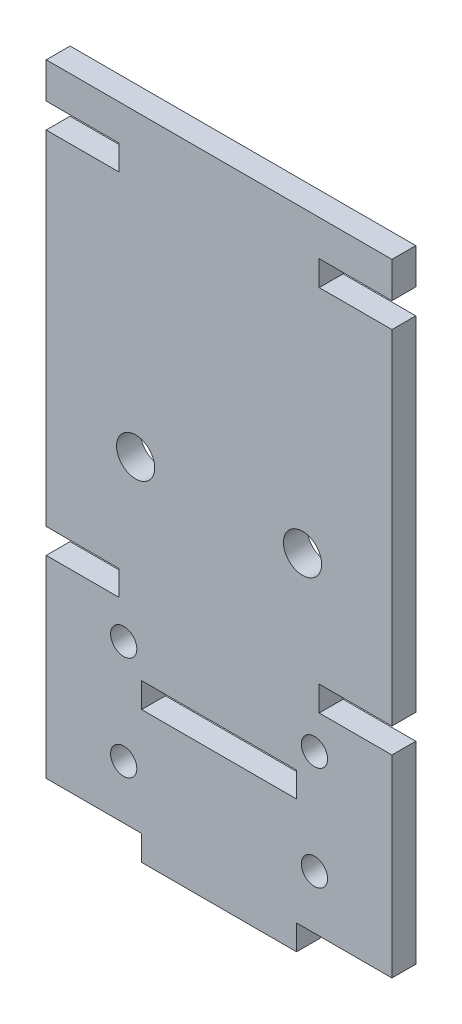
SolidWorks part; units mm, degrees
ref_plane "前视基准面" through (0, 0, 0) normal (0, 0, 1) x (1, 0, 0)
ref_plane "上视基准面" through (0, 0, 0) normal (0, 1, 0) x (1, 0, 0)
ref_plane "右视基准面" through (0, 0, 0) normal (1, 0, 0) x (0, 0, -1)
other "Configuration Table"
sketch "草图1" plane through (0, 0, 0) normal (0, 0, 1) x (1, 0, 0)
  line L0 (-12.2429, -15.7995) -> (16.7571, -15.7995)
  line L1 (16.7571, -15.7995) -> (16.7571, 31.3005)
  line L2 (16.7571, 31.3005) -> (-12.2429, 31.3005)
  line L3 (-12.2429, 31.3005) -> (-12.2429, -15.7995)
  line L4 (34.6769, 7.7505) -> (-34.6769, 7.7505) construction
  line L5 (2.2571, 33.4458) -> (2.2571, -33.4458) construction
  line L6 (-4.2429, -15.7995) -> (-4.2429, -17.8995)
  line L7 (-4.2429, -17.8995) -> (8.7571, -17.8995)
  line L8 (8.7571, -15.7995) -> (8.7571, -17.8995)
  line L9 (-4.2429, -4.6995) -> (-12.2429, -4.6995)
  line L10 (-4.2429, -4.6995) -> (-4.2429, -6.7995)
  line L11 (-4.2429, -6.7995) -> (-12.2429, -6.7995)
  line L12 (8.7571, -6.7995) -> (16.7571, -6.7995)
  line L13 (8.7571, -4.6995) -> (16.7571, -4.6995)
  line L14 (8.7571, -4.6995) -> (8.7571, -6.7995)
  line L15 (-4.2429, -6.7995) -> (8.7571, -6.7995)
  line L16 (-4.2429, -4.6995) -> (8.7571, -4.6995)
  point P12 (2.2571, -17.8995)
  dimension "D1" = 29
  dimension "D2" = 2.1
  dimension "D3" = 8
  dimension "D4" = 2.1
  dimension "D5" = 9
  dimension "D6" = 36
extrude "凸台-拉伸1" add sketch "草图1" along normal blind 2 contours L9 L16 L13 L1 L2 L3 | L15 L11 L3 L0 L1 L12 | L13 L14 L12 L1 | L11 L10 L9 L3 | L8 L0 L6 L7
sketch "草图2" plane through (0, 0, 2) normal (0, 0, 1) x (1, 0, 0)
  line L0 (2.2571, -4.6995) -> (2.2571, 37.8444) construction
  line L1 (8.7571, -4.6995) -> (-4.2429, -4.6995) construction
  line L2 (16.7571, 2.5005) -> (10.6571, 2.5005)
  line L3 (16.7571, -15.7995) -> (16.7571, 31.3005) construction
  line L4 (10.6571, 2.5005) -> (10.6571, 0.4005)
  line L5 (10.6571, 0.4005) -> (16.7571, 0.4005)
  line L7 (-6.1429, 2.5005) -> (-6.1429, 0.4005)
  line L8 (-6.1429, 0.4005) -> (-12.2429, 0.4005)
  line L9 (-6.1429, 2.5005) -> (-12.2429, 2.5005)
  line L10 (-12.2429, 31.3005) -> (-12.2429, -15.7995) construction
  line L11 (-12.2429, 2.5005) -> (-12.2429, 0.4005)
  line L12 (16.7571, 2.5005) -> (16.7571, 0.4005)
  dimension "D1" = 2.1
  dimension "D2" = 6.1
  dimension "D3" = 5.1
extrude "切除-拉伸1" cut sketch "草图2" against normal blind 2 contours L11 L8 L7 L9 | L12 L5 L4 L2
sketch "草图3" plane through (0, 0, 2) normal (0, 0, 1) x (1, 0, 0)
  line L0 (-6.1429, 31.3005) -> (-6.1429, 33.4005)
  line L1 (16.7571, 31.3005) -> (-12.2429, 31.3005) construction
  line L2 (-6.1429, 33.4005) -> (10.6571, 33.4005)
  line L3 (2.2571, 31.3005) -> (2.2571, 42.1871) construction
  line L4 (10.6571, 31.3005) -> (10.6571, 33.4005)
  line L5 (-6.1429, 31.3005) -> (10.6571, 31.3005)
  point P10 (2.2571, 33.4005)
  dimension "D1" = 2.1
  dimension "D2" = 16.8
extrude "凸台-拉伸2" add sketch "草图3" against normal blind 2 contours L5 L4 L2 L0
sketch "草图4" plane through (0, 0, 2) normal (0, 0, 1) x (1, 0, 0)
  line L0 (2.2571, -4.6995) -> (2.2571, 42.1555) construction
  line L1 (8.7571, -4.6995) -> (-4.2429, -4.6995) construction
  line L2 (-6.1429, 31.3005) -> (-12.2429, 31.3005) construction
  circle A0 centre (-4.7429, 11.3005) radius 1.6
  circle A1 centre (9.2571, 11.3005) radius 1.6
  dimension "D1" = 3.2
  dimension "D2" = 14
  dimension "D3" = 20
extrude "切除-拉伸2" cut sketch "草图4" against normal blind 2
sketch "草图5" plane through (0, 0, 0) normal (0, 0, -1) x (-1, 0, 0)
  circle A0 centre (-10.2571, -2.5995) radius 1.1
  circle A1 centre (5.7429, -2.5995) radius 1.1
extrude "切除-拉伸5" cut sketch "草图5" against normal blind 10
sketch "草图6" plane through (0, 0, 2) normal (0, 0, 1) x (1, 0, 0)
  line L0 (2.2571, -4.6995) -> (2.2571, -22.9249) construction
  line L1 (8.7571, -4.6995) -> (-4.2429, -4.6995) construction
  line L2 (23.045, -11.2995) -> (-21.3219, -11.2995) construction
  line L3 (-4.2429, -6.7995) -> (8.7571, -6.7995) construction
  line L4 (8.7571, -15.7995) -> (16.7571, -15.7995) construction
  circle A0 centre (10.2571, -11.2995) radius 1.1
  circle A1 centre (-5.7429, -11.2995) radius 1.1
  point P12 (0, 0)
  dimension "D2" = 2.2
  dimension "D1" = 16
extrude "切除-拉伸6" cut sketch "草图6" against normal blind 10
sketch "草图7" plane through (0, 0, 2) normal (0, 0, 1) x (1, 0, 0)
  line L0 (-6.1429, 33.4005) -> (-12.2429, 33.4005)
  line L1 (-12.2429, 33.4005) -> (-12.2429, 36.4005)
  line L2 (-12.2429, 36.4005) -> (16.7571, 36.4005)
  line L3 (16.7571, 36.4005) -> (16.7571, 33.4005)
  line L4 (16.7571, 33.4005) -> (-6.1429, 33.4005)
  line L5 (16.7571, 2.5005) -> (16.7571, 31.3005) construction
  line L6 (-12.2429, 31.3005) -> (-12.2429, 2.5005) construction
  dimension "D1" = 3
extrude "凸台-拉伸3" add sketch "草图7" against normal blind 2
